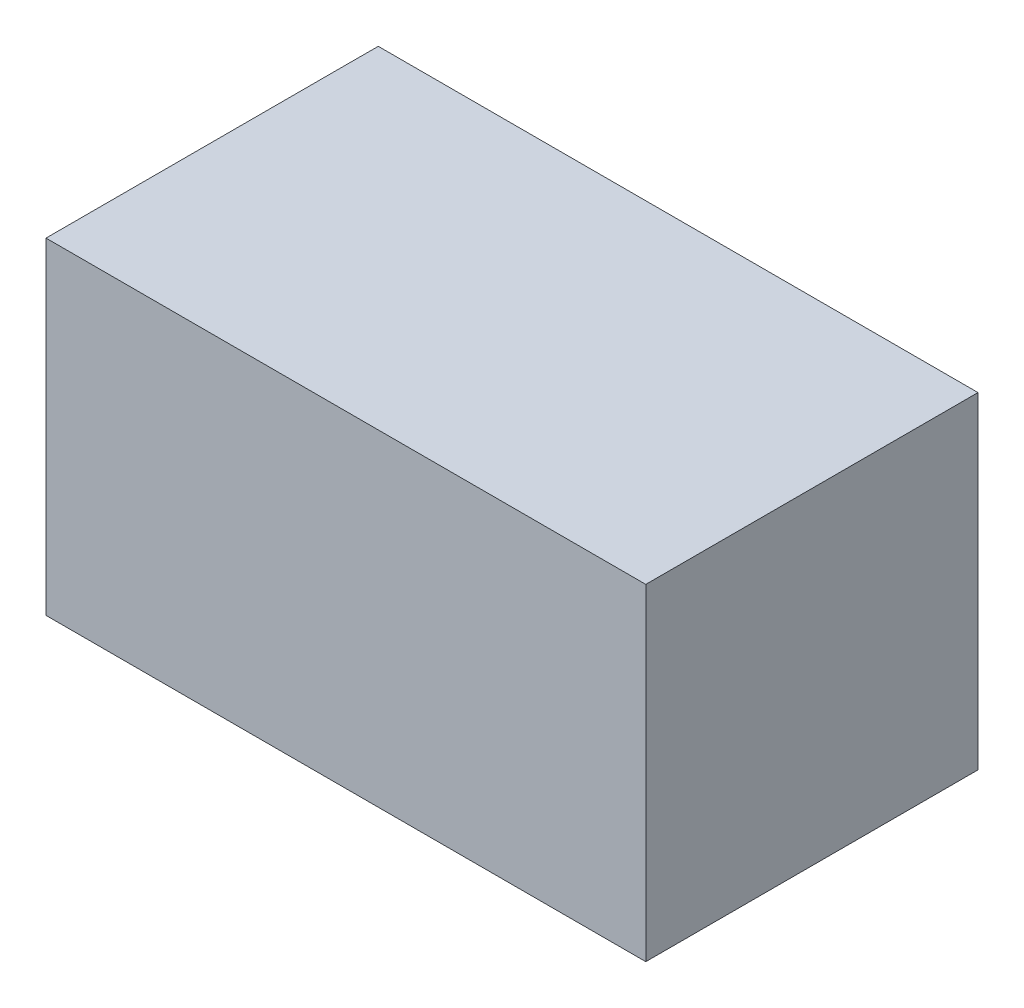
SolidWorks part; units mm, degrees
ref_plane "前基準面" through (0, 0, 0) normal (0, 0, 1) x (1, 0, 0)
ref_plane "上基準面" through (0, 0, 0) normal (0, 1, 0) x (1, 0, 0)
ref_plane "右基準面" through (0, 0, 0) normal (1, 0, 0) x (0, 0, -1)
sketch "草圖1" plane through (0, 0, 0) normal (0, 0, 1) x (1, 0, 0)
  line L1 (-41, 15) -> (41, 15)
  line L2 (-41, 15) -> (-41, -15)
  line L3 (-41, -15) -> (41, -15)
  line L4 (41, 15) -> (41, -15)
  line L5 (-41, 15) -> (41, -15) construction
  line L6 (-41, -15) -> (41, 15) construction
  point P0 (0, 0)
  dimension "D1" = 82
  dimension "D2" = 30
extrude "填料-伸長1" add sketch "草圖1" along normal blind 1.5
sketch "草圖2" plane through (0, 0, 0) normal (0, 0, -1) x (-1, 0, 0)
  line L0 (41, 12.8993) -> (41, -12.8993)
  line L1 (41, 15) -> (41, -15) construction
  line L2 (41, 12.8993) -> (39.0024, 12.8993)
  line L3 (39.0024, 12.8993) -> (39.0024, -12.8993)
  line L4 (39.0024, -12.8993) -> (41, -12.8993)
  point P5 (41, 0)
extrude "填料-伸長3" add sketch "草圖2" along normal blind 3.5
sketch "草圖4" plane through (-39.0024, 0, 0) normal (1, 0, 0) x (0, 0, -1)
  line L0 (0, 12.8993) -> (1.75, 12.8993)
  line L1 (3.5, 12.8993) -> (0, 12.8993) construction
  line L2 (1.75, 12.8993) -> (1.75, -12.8993)
  line L3 (3.5, -12.8993) -> (0, -12.8993) construction
  line L4 (1.75, -12.8993) -> (3.5, -12.8993)
  line L5 (3.5, -12.8993) -> (3.5, 12.8993)
  line L6 (3.5, 12.8993) -> (1.75, 12.8993)
  line M2 (0, -12.8993) -> (3.5, -12.8993)
  line M3 (3.5, -12.8993) -> (3.5, 12.8993)
  line M4 (3.5, 12.8993) -> (0, 12.8993)
extrude "填料-伸長4" add sketch "草圖4" along normal blind 26 contours L2 M4 M2 M3
sketch "草圖5" plane through (0, 0, 1.5) normal (0, 0, 1) x (1, 0, 0)
  line L0 (41, 15) -> (41, -15)
  line L1 (41, -15) -> (-14.0641, -15)
  line L2 (-41, -15) -> (41, -15) construction
  line L3 (-14.0641, -15) -> (-14.0641, 15)
  line L4 (41, 15) -> (-41, 15) construction
  line L5 (-14.0641, 15) -> (41, 15)
extrude "填料-伸長5" add sketch "草圖5" along normal blind 29
sketch "草圖6" plane through (-14.0641, 0, 0) normal (-1, 0, 0) x (0, 0, 1)
  line L0 (2.8174, 14.0374) -> (2.8174, -14.1576)
  line L3 (2.8174, 14.0374) -> (29.1701, 14.0374)
  line L4 (29.1701, 14.0374) -> (29.1701, -14.1576)
  line L5 (29.1701, -14.1576) -> (2.8174, -14.1576)
extrude "除料-伸長1" cut sketch "草圖6" against normal blind 53
sketch "草圖8" plane through (0, 0, 2.8174) normal (0, 0, 1) x (1, 0, 0)
  line L0 (-14.0641, 14.0374) -> (38.9359, 14.0374)
  line L1 (38.9359, 14.0374) -> (38.9359, -14.1576)
  line L2 (38.9359, -14.1576) -> (-14.0641, -14.1576) construction
  line L3 (38.9359, 14.0374) -> (38.9359, -14.1576) construction
  line L4 (38.9359, -14.1576) -> (-14.0641, -14.1576)
  line L5 (-14.0641, -14.1576) -> (-14.0641, 14.0374)
extrude "除料-伸長2" cut sketch "草圖8" against normal blind 1.32
sketch "草圖10" plane through (-41, 0, 0) normal (-1, 0, 0) x (0, 0, 1)
  line L0 (1.5, 15) -> (1.5, -16.0799)
  line L1 (1.5, -16.0799) -> (-4.3575, -16.0799)
  line L2 (-4.3575, -16.0799) -> (-4.3575, 16.2401)
  line L3 (-4.3575, 16.2401) -> (1.5, 16.2401)
  line L4 (1.5, 16.2401) -> (1.5, 15)
extrude "除料-伸長5" cut sketch "草圖10" against normal blind 26.94
sketch "草圖11" plane through (-14.06, 0, 0) normal (-1, 0, 0) x (0, 0, 1)
  line L0 (-1.75, 12.8993) -> (-3.5, 12.8993)
  line L1 (-3.5, 12.8993) -> (-4.7494, -13.677)
  line L2 (-4.7494, -13.677) -> (-1.2651, -13.677)
  line L3 (-1.2651, -13.677) -> (-1.2651, 12.8993)
  line L4 (-1.2651, 12.8993) -> (-1.75, 12.8993)
extrude "除料-伸長6" cut sketch "草圖11" against normal blind 26.94
